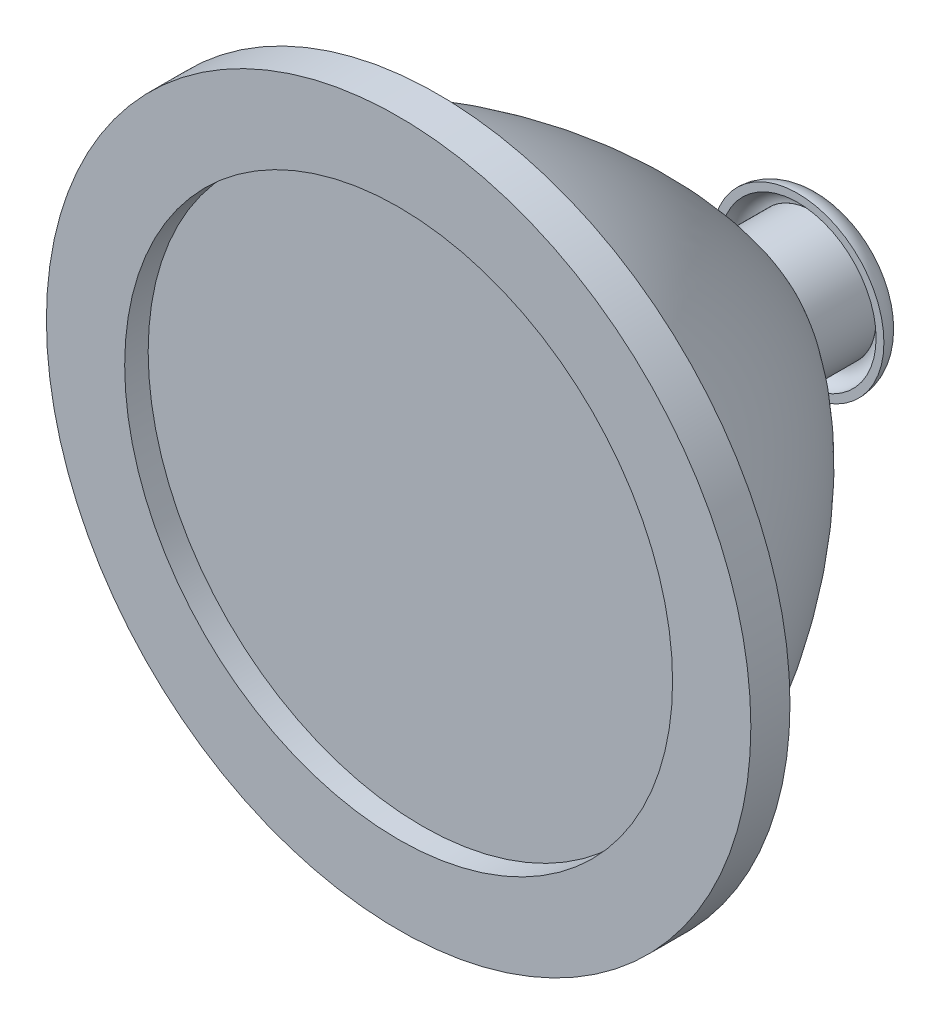
SolidWorks part; units mm, degrees
ref_plane "Front Plane" through (0, 0, 0) normal (0, 0, 1) x (1, 0, 0)
ref_plane "Top Plane" through (0, 0, 0) normal (0, 1, 0) x (1, 0, 0)
ref_plane "Right Plane" through (0, 0, 0) normal (1, 0, 0) x (0, 0, -1)
sketch "Sketch1" plane through (0, 0, 0) normal (1, 0, 0) x (0, 0, -1)
  line L0 (-43.7307, 0) -> (54.5812, 0) construction
  line L1 (0, 0) -> (0, 50.8)
  line L3 (0, 0) -> (50.8, 0)
  line L4 (50.8, 0) -> (50.8, 10.16)
  arc A0 (0, 50.8) -> (50.8, 10.16) centre (-34.7283, -44.6804) cw
  dimension "D3" = 101.6
  dimension "D1" = 50.8
  dimension "D2" = 10.16
revolve "BaseRevolve" add sketch "Sketch1" angle 360 about L0
shell "LensShell" thickness 6.35
sketch "Sketch2" plane through (0, 0, -50.8) normal (0, 0, -1) x (-1, 0, 0)
  circle A1 centre (0, 0) radius 10.16
  circle A2 centre (0, 0) radius 10.16
  dimension "D1" = 0
extrude "LensNeck" add sketch "Sketch2" along normal blind 10.16
hole_wizard "BulbHole" positions "Sketch17" profile "Sketch18" counterbore size "1/2" standard "ANSI Inch" end condition through all
sketch "Sketch17" plane through (0, 0, -44.45) normal (0, 0, 1) x (1, 0, 0)
  point P0 (0, 0)
  point P3 (0, 0)
sketch "Sketch18" plane through (0, 0, -44.45) normal (1, 0, 0) x (0, -1, 0)
  line L0 (0, 0) -> (0, 16.51)
  line L1 (0, 16.51) -> (6.7462, 16.51)
  line L3 (6.7462, 16.51) -> (6.7462, 5.08)
  line L4 (6.7462, 5.08) -> (7.62, 5.08)
  line L5 (7.62, 5.08) -> (7.62, 0)
  line L7 (7.62, 0) -> (0, 0)
  line L11 (0, -6.35) -> (0, 107.95) construction
  dimension "Thru Hole Dia." = 13.4925
  dimension "Thru Hole Depth" = 16.51
  dimension "C'Bore Dia." = 15.24
  dimension "C'Bore Depth" = 5.08
sketch "Sketch19" plane through (0, 0, 0) normal (1, 0, 0) x (0, 0, -1)
  line L0 (60.96, 10.16) -> (50.8, 10.16) construction
  arc A0 (60.96, 10.16) -> (58.42, 12.7) centre (58.42, 10.16) ccw
  dimension "D1" = 2.54
revolve "LensConnector" add sketch "Sketch19" angle 360 about L3
sketch "Sketch20" plane through (0, 0, 0) normal (0, 0, 1) x (1, 0, 0)
  circle A2 centre (0, 0) radius 57.15
  circle A3 centre (0, 0) radius 57.15
  circle A4 centre (0, 0) radius 44.45
  circle A5 centre (0, 0) radius 44.45
  dimension "D1" = 6.35
  dimension "D2" = 6.35
extrude "LensCover" add sketch "Sketch20" along normal blind 6.35
sketch "Sketch22" plane through (0, 0, 0) normal (0, 0, 1) x (1, 0, 0)
  circle A0 centre (0, 0) radius 44.45 construction
  circle A1 centre (0, 0) radius 44.45
extrude "LensShield" add sketch "Sketch22" along normal blind 2.54
